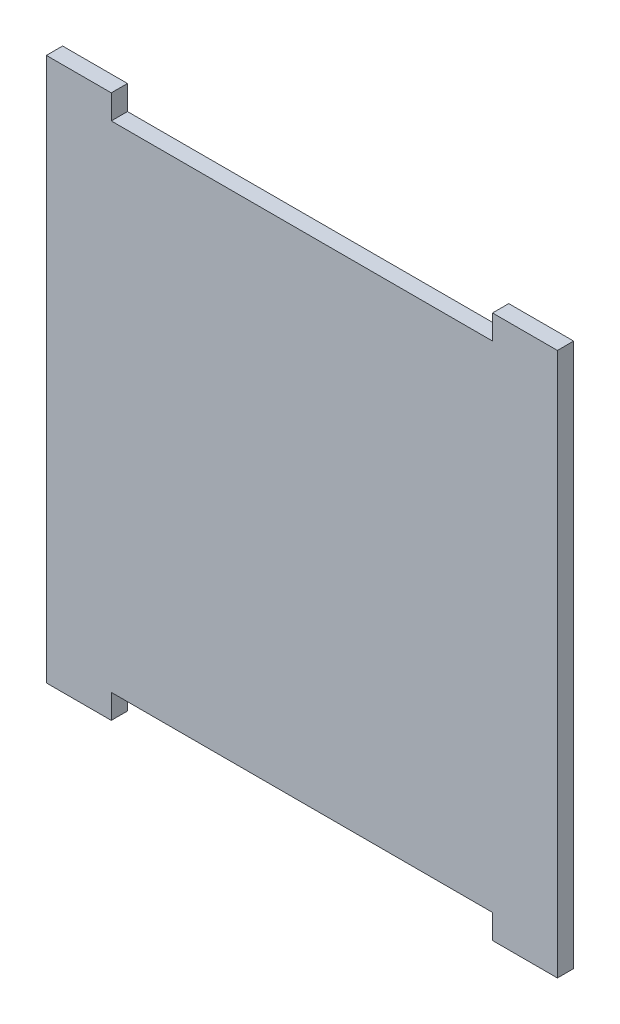
SolidWorks part; units mm, degrees
ref_plane "Front Plane" through (0, 0, 0) normal (0, 0, 1) x (1, 0, 0)
ref_plane "Top Plane" through (0, 0, 0) normal (0, 1, 0) x (1, 0, 0)
ref_plane "Right Plane" through (0, 0, 0) normal (1, 0, 0) x (0, 0, -1)
sketch "Sketch1" plane through (0, 0, 0) normal (0, 0, 1) x (1, 0, 0)
  line L0 (65.0875, -80.9625) -> (-65.0875, -80.9625) construction
  line L1 (-93.6625, -106.3625) -> (106.3625, -106.3625)
  line L2 (-93.6625, -106.3625) -> (-93.6625, 106.3625)
  line L3 (-93.6625, 106.3625) -> (106.3625, 106.3625)
  line L4 (106.3625, -106.3625) -> (106.3625, 106.3625)
  line L5 (-65.0875, 80.9625) -> (65.0875, 80.9625) construction
  line L6 (80.9625, 65.0875) -> (80.9625, -65.0875) construction
  line L7 (-80.9625, -65.0875) -> (-80.9625, 65.0875) construction
  dimension "D1" = 25.4
  dimension "D2" = 25.4
  dimension "D3" = 25.4
  dimension "D4" = 12.7
extrude "Extrude1" add sketch "Sketch1" along normal blind 6.35
sketch "Sketch2" plane through (0, 0, 6.35) normal (0, 0, 1) x (1, 0, 0)
  line L0 (-93.6625, -106.3625) -> (106.3625, -106.3625) construction
  line L1 (-68.2625, -106.3625) -> (80.9625, -106.3625)
  line L2 (-68.2625, -106.3625) -> (-68.2625, -96.8375)
  line L3 (-68.2625, -96.8375) -> (80.9625, -96.8375)
  line L4 (80.9625, -106.3625) -> (80.9625, -96.8375)
  line L5 (80.9625, -96.8375) -> (106.3625, -96.8375) construction
  line L6 (106.3625, -106.3625) -> (106.3625, 106.3625) construction
  line L7 (-68.2625, -96.8375) -> (-93.6625, -96.8375) construction
  line L8 (-93.6625, 106.3625) -> (-93.6625, -106.3625) construction
  dimension "D1" = 25.4
  dimension "D2" = 9.525
extrude "Cut-Extrude1" cut sketch "Sketch2" against normal up to next
mirror "Mirror1" about plane through (0, 0, 0) normal (0, 1, 0) of "Cut-Extrude1"
